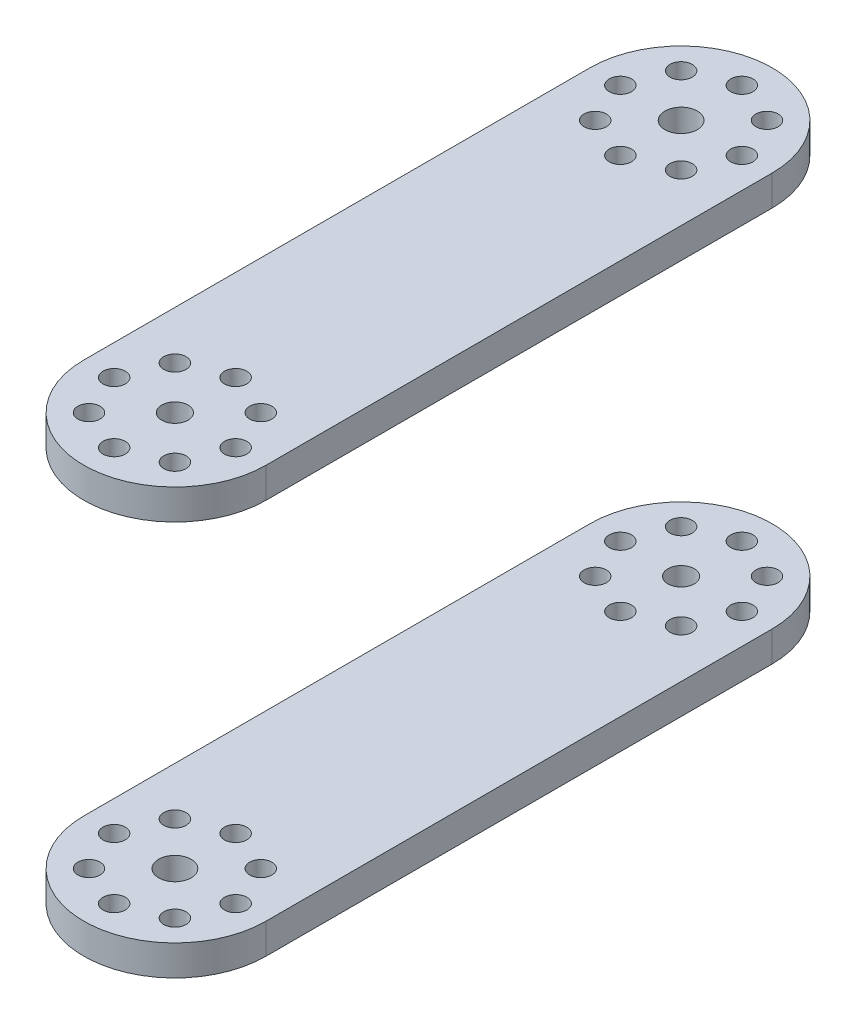
SolidWorks part; units mm, degrees
material "ABS"
ref_plane "正面" through (0, 0, 0) normal (0, 0, 1) x (1, 0, 0)
ref_plane "平面" through (0, 0, 0) normal (0, 1, 0) x (1, 0, 0)
ref_plane "右側面" through (0, 0, 0) normal (1, 0, 0) x (0, 0, -1)
sketch "ｽｹｯﾁ1" plane through (0, 0, 0) normal (0, 1, 0) x (1, 0, 0)
  line L0 (-9, 50) -> (-9, 0)
  line L2 (-10.5, 10.5) -> (-10.5, -10.5) construction
  line L8 (9, 0) -> (9, 50)
  arc A4 (9, 50) -> (-9, 50) centre (0, 50) ccw
  circle A5 centre (0, 50) radius 6 construction
  circle A6 centre (0, 56) radius 1.1
  circle A7 centre (4.2426, 54.2426) radius 1.1
  circle A8 centre (6, 50) radius 1.1
  circle A9 centre (4.2426, 45.7574) radius 1.1
  circle A10 centre (0, 44) radius 1.1
  circle A11 centre (-4.2426, 45.7574) radius 1.1
  circle A12 centre (-6, 50) radius 1.1
  circle A13 centre (-4.2426, 54.2426) radius 1.1
  circle A14 centre (0, 50) radius 1.6
  circle A15 centre (0, 0) radius 1.3
  arc A16 (-9, 0) -> (9, 0) centre (0, 0) ccw
  circle A17 centre (0, 0) radius 6 construction
  circle A18 centre (0, 6) radius 1.1
  circle A19 centre (4.2426, 4.2426) radius 1.1
  circle A20 centre (6, 0) radius 1.1
  circle A21 centre (4.2426, -4.2426) radius 1.1
  circle A22 centre (0, -6) radius 1.1
  circle A23 centre (-4.2426, -4.2426) radius 1.1
  circle A24 centre (-6, 0) radius 1.1
  circle A25 centre (-4.2426, 4.2426) radius 1.1
  point P35 (0, 50)
  point P48 (0, 0)
  dimension "D2" = 9
  dimension "D3" = 2.6
  dimension "D4" = 50
  dimension "D5" = 12
  dimension "D10" = 12
  dimension "D11" = 2.2
  dimension "D13" = 3.2
  dimension "D6" = 2.2
  dimension "D7" = 8
  dimension "D12" = 8
extrude "ﾎﾞｽ - 押し出し1" add sketch "ｽｹｯﾁ1" along normal blind 3
ref_plane "平面1" through (0, -36, 0) normal (0, 1, 0) x (1, 0, 0)
sketch "ｽｹｯﾁ2" plane through (0, -36, 0) normal (0, 1, 0) x (1, 0, 0)
  line L3 (9, 0) -> (9, 50)
  line L5 (-9, 50) -> (-9, 0)
  line L6 (9, 0) -> (9, 50)
  line L8 (-9, 50) -> (-9, 0)
  circle A0 centre (0, 50) radius 1.3
  arc A1 (9, 50) -> (-9, 50) centre (0, 50) ccw
  arc A2 (9, 50) -> (-9, 50) centre (0, 50) ccw
  circle A3 centre (0, 50) radius 6 construction
  circle A4 centre (0, 56) radius 1.1
  circle A5 centre (4.2426, 54.2426) radius 1.1
  circle A6 centre (6, 50) radius 1.1
  circle A12 centre (0, 0) radius 1.6
  arc A13 (-9, 0) -> (9, 0) centre (0, 0) ccw
  arc A14 (-9, 0) -> (9, 0) centre (0, 0) ccw
  circle A15 centre (0, 0) radius 6 construction
  circle A16 centre (0, 6) radius 1.1
  circle A17 centre (4.2426, 4.2426) radius 1.1
  circle A18 centre (6, 0) radius 1.1
  circle A19 centre (4.2426, -4.2426) radius 1.1
  circle A20 centre (0, -6) radius 1.1
  circle A21 centre (-4.2426, -4.2426) radius 1.1
  circle A22 centre (-6, 0) radius 1.1
  circle A23 centre (-4.2426, 4.2426) radius 1.1
  circle A24 centre (4.2426, 45.7574) radius 1.1
  circle A25 centre (0, 44) radius 1.1
  circle A26 centre (-4.2426, 45.7574) radius 1.1
  circle A27 centre (-6, 50) radius 1.1
  circle A28 centre (-4.2426, 54.2426) radius 1.1
  circle A29 centre (0, 0) radius 1.3 construction
  point P30 (0, 0)
  point P48 (0, 50)
  dimension "D2" = 2.6
  dimension "D3" = 12
  dimension "D4" = 2.2
  dimension "D5" = 12
  dimension "D6" = 8
  dimension "D7" = 2.2
  dimension "D8" = 3.2
  dimension "D1" = 0
extrude "ﾎﾞｽ - 押し出し2" add sketch "ｽｹｯﾁ2" against normal blind 3 separate body
